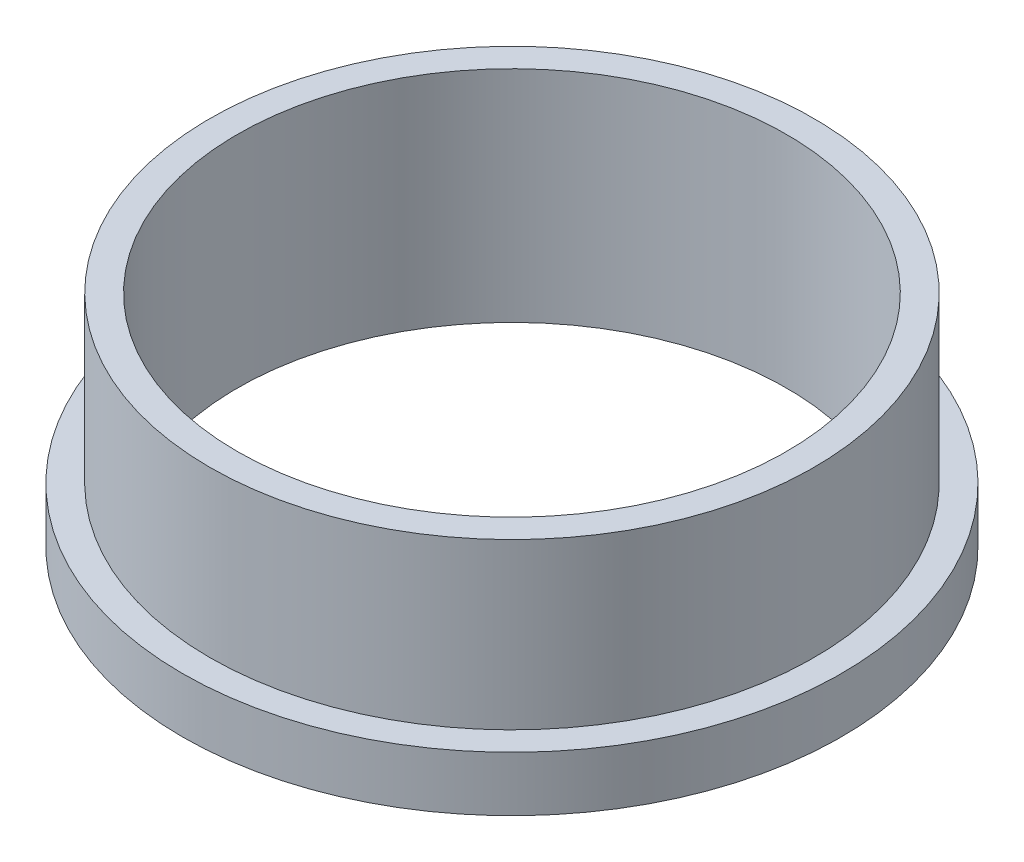
SolidWorks part; units mm, degrees
ref_plane "Front Plane" through (0, 0, 0) normal (0, 0, 1) x (1, 0, 0)
ref_plane "Top Plane" through (0, 0, 0) normal (0, 1, 0) x (1, 0, 0)
ref_plane "Right Plane" through (0, 0, 0) normal (1, 0, 0) x (0, 0, -1)
sketch "Sketch1" plane through (0, 0, 0) normal (0, 1, 0) x (1, 0, 0)
  circle A0 centre (0, 0) radius 25
  circle A1 centre (0, 0) radius 30
  dimension "D1" = 50
  dimension "D2" = 60
extrude "Boss-Extrude1" add sketch "Sketch1" along normal blind 20
sketch "Sketch2" plane through (0, 20, 0) normal (0, 1, 0) x (1, 0, 0)
  circle A0 centre (0, 0) radius 27.5
  circle A1 centre (0, 0) radius 25 construction
  circle A2 centre (0, 0) radius 17.5
  circle A3 centre (0, 0) radius 30
  circle M1 centre (0, 0) radius 30
  dimension "D1" = 2.5
extrude "Cut-Extrude2" cut sketch "Sketch2" against normal blind 15 contours A0 M1
